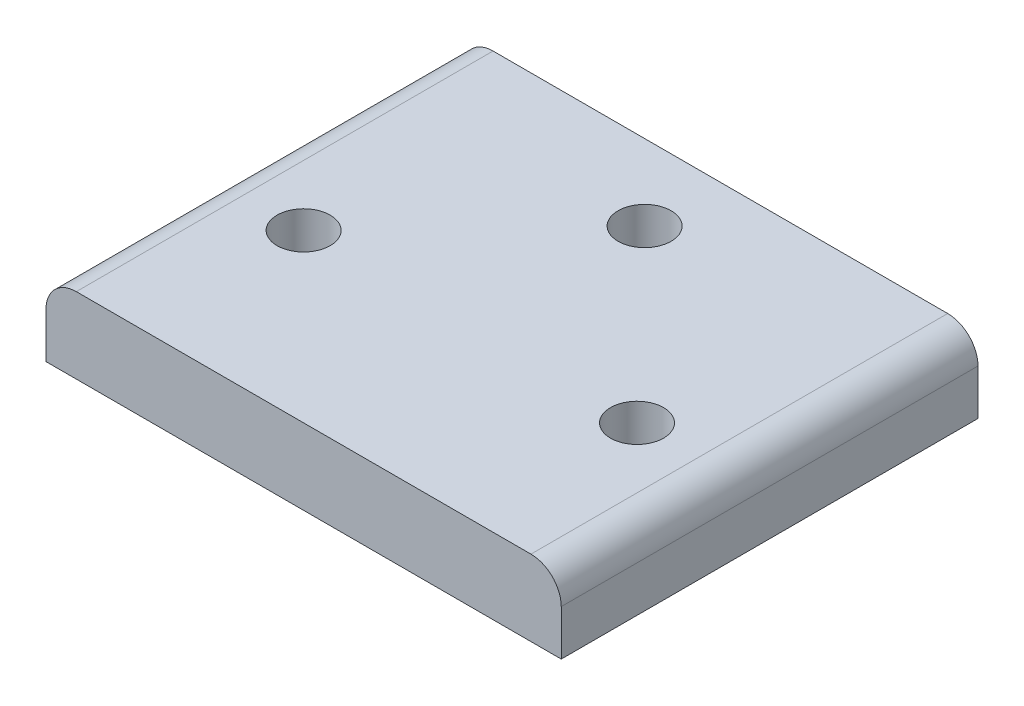
SolidWorks part; units mm, degrees
ref_plane "Front Plane" through (0, 0, 0) normal (0, 0, 1) x (1, 0, 0)
ref_plane "Top Plane" through (0, 0, 0) normal (0, 1, 0) x (1, 0, 0)
ref_plane "Right Plane" through (0, 0, 0) normal (1, 0, 0) x (0, 0, -1)
sketch "Sketch1" plane through (0, 0, 0) normal (0, 1, 0) x (1, 0, 0)
  line L1 (-17, -13.75) -> (17, -13.75)
  line L2 (-17, -13.75) -> (-17, 13.75)
  line L3 (-17, 13.75) -> (17, 13.75)
  line L4 (17, -13.75) -> (17, 13.75)
  line L5 (-17, -13.75) -> (17, 13.75) construction
  line L6 (-17, 13.75) -> (17, -13.75) construction
  circle A0 centre (0, 8.75) radius 1.75
  circle A1 centre (-11, -2.75) radius 1.75
  circle A2 centre (11, -2.75) radius 1.75
  point P0 (0, 0)
  dimension "D7" = 3.5
  dimension "D1" = 34
  dimension "D2" = 27.5
  dimension "D3" = 5
  dimension "D4" = 11
  dimension "D5" = 11
  dimension "D6" = 11
extrude "Boss-Extrude1" add sketch "Sketch1" along normal blind 5
fillet "Fillet1" radius 2 2 edges at (-17, 5, 0) (17, 5, 0)
sketch "Sketch2" plane through (0, 0, 0) normal (0, -1, 0) x (1, 0, 0)
  circle A0 centre (-5.3, 7.5) radius 5.25
  circle A1 centre (5.3, 7.5) radius 5.25
  circle A2 centre (0, -1.7) radius 5.25
  dimension "D1" = 10.5
  dimension "D2" = 1.7
  dimension "D3" = 5.3
  dimension "D4" = 5.3
  dimension "D5" = 7.5
extrude "Cut-Extrude1" cut sketch "Sketch2" against normal blind 0.4
